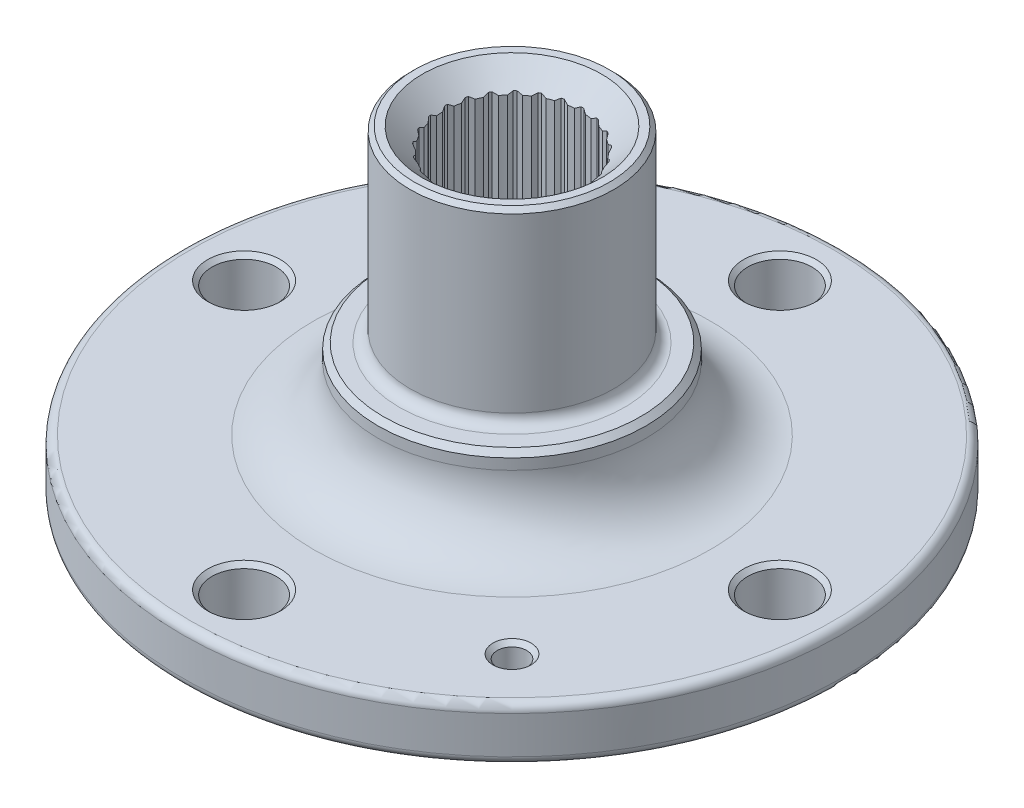
SolidWorks part; units mm, degrees
ref_plane "Plano frontal" through (0, 0, 0) normal (0, 0, 1) x (1, 0, 0)
ref_plane "Plano superior" through (0, 0, 0) normal (0, 1, 0) x (1, 0, 0)
ref_plane "Plano direito" through (0, 0, 0) normal (1, 0, 0) x (0, 0, -1)
sketch "Esboço1" plane through (0, 0, 0) normal (0, 0, 1) x (1, 0, 0)
  line L0 (0, -42.6779) -> (0, 53.2086) construction
  line L1 (12.75, 53.2086) -> (19, 53.2086)
  line L2 (19, 53.2086) -> (19, 18.2086)
  line L3 (19, 18.2086) -> (25, 18.2086)
  line L4 (25, 18.2086) -> (25, 3.2086)
  line L5 (25, 3.2086) -> (61.5, 3.2086)
  line L6 (61.5, 3.2086) -> (61.5, -6.7914)
  line L7 (61.5, -6.7914) -> (31, -6.7914)
  line L8 (31, -6.7914) -> (31, -12.7914)
  line L9 (31, -12.7914) -> (27, -12.7914)
  line L10 (27, -12.7914) -> (27, -23.7914)
  line L11 (27, -23.7914) -> (24, -23.7914)
  line L12 (24, -23.7914) -> (24, 0)
  line L13 (24, 0) -> (12.75, 0)
  line L14 (12.75, 0) -> (12.75, 53.2086)
  dimension "D1" = 12.75
  dimension "D2" = 19
  dimension "D3" = 35
  dimension "D4" = 50
  dimension "D5" = 61.5
  dimension "D6" = 24
  dimension "D7" = 31
  dimension "D8" = 27
  dimension "D9" = 10
  dimension "D10" = 6
  dimension "D11" = 17
  dimension "D12" = 25
revolve "Revolução1" add sketch "Esboço1" angle 360 about L0
fillet "Filete1" radius 12 1 edges at (0, 3.2086, -25)
fillet "Filete2" radius 2 1 edges at (0, 18.2086, -19)
chamfer "Chanfro1" distance 0.8 angle 45 1 edges at (0, 53.2086, -19)
sketch "Esboço2" plane through (0, -6.7914, 0) normal (0, -1, 0) x (1, 0, 0)
  circle A0 centre (0, 0) radius 50 construction
  circle A1 centre (0, 50) radius 6
  circle A2 centre (-35.3553, -35.3553) radius 2.75
  circle A3 centre (50, 0) radius 6
  circle A4 centre (35.3553, 35.3553) radius 2.75
  circle A5 centre (0, -50) radius 6
  circle A7 centre (-50, 0) radius 6
  circle A9 centre (-35.3553, 35.3553) radius 6 [skipped]
  circle A10 centre (35.3553, -35.3553) radius 6 [skipped]
  circle A11 centre (35.3553, 35.3553) radius 6 [skipped]
  circle A12 centre (-35.3553, -35.3553) radius 6 [skipped]
  point P21 (0, 0)
  dimension "D1" = 100
  dimension "D2" = 12
  dimension "D4" = 5.5
  dimension "D3" = 8
extrude "Corte-extrusão1" cut sketch "Esboço2" against normal through all
chamfer "Chanfro2" distance 0.8 angle 45 12 edges at (0, -6.7914, -56) (0, 3.2086, -44) (50, -6.7914, -6) (50, 3.2086, 6) (35.3553, 3.2086, 38.1053) (35.3553, -6.7914, 32.6053) (-35.3553, -6.7914, -38.1053) (-35.3553, 3.2086, -32.6053) (-50, -6.7914, -6) (-50, 3.2086, 6) (0, -6.7914, 44) (0, 3.2086, 56)
fillet "Filete3" radius 1.5 1 edges at (0, -6.7914, -61.5)
fillet "Filete4" radius 1.5 1 edges at (0, 3.2086, -61.5)
chamfer "Chanfro3" distance 1 angle 45 1 edges at (0, 18.2086, -25)
fillet "Filete5" radius 1.5 1 edges at (0, -6.7914, -31)
chamfer "Chanfro4" distance 0.8 angle 45 3 edges at (0, -23.7914, -24) (0, -23.7914, -27) (0, -12.7914, -31)
fillet "Filete6" radius 2 1 edges at (0, -12.7914, -27)
chamfer "Chanfro5" distance 4 angle 45 1 edges at (0, 53.2086, -12.75)
chamfer "Chanfro6" distance 0.5 angle 30 1 edges at (0, 0, -12.75)
fillet "Filete7" radius 1.5 1 edges at (0, 0, -24)
sketch "Esboço3" plane through (0, 53.2086, 0) normal (0, 1, 0) x (1, 0, 0)
sketch "Esboço4" plane through (0, 53.2086, 0) normal (0, 1, 0) x (1, 0, 0)
  line L0 (2.1924, 12.5601) -> (3.0275, 12.7967)
  line L1 (-1, 12.7107) -> (-0.25, 13.1476)
  line L2 (0.25, 13.1476) -> (1, 12.7107)
  line L3 (3.5118, 12.6724) -> (4.1296, 12.0627)
  line L4 (5.2471, 11.6202) -> (6.1148, 11.6418)
  line L5 (6.553, 11.4009) -> (6.9997, 10.6567)
  line L6 (7.9721, 9.9503) -> (8.8179, 9.7553)
  line L7 (9.1824, 9.4131) -> (9.4301, 8.5812)
  line L8 (10.1962, 7.6551) -> (10.9669, 7.2559)
  line L9 (11.2349, 6.8338) -> (11.2678, 5.9664)
  line L10 (11.7796, 4.8789) -> (12.4269, 4.3006)
  line L11 (12.5814, 3.8251) -> (12.3976, 2.9768)
  line L12 (12.6229, 1.7961) -> (13.106, 1.0751)
  line L13 (13.1374, 0.576) -> (12.7484, -0.1999)
  line L14 (12.673, -1.3995) -> (12.9616, -2.218)
  line L15 (12.8679, -2.7092) -> (12.2982, -3.364)
  line L16 (11.9268, -4.5071) -> (12.0028, -5.3718)
  line L17 (11.7899, -5.8242) -> (11.0752, -6.3168)
  line L18 (10.4312, -7.3316) -> (10.2898, -8.188)
  line L19 (9.9711, -8.5732) -> (9.1564, -8.8726)
  line L20 (8.2802, -9.6954) -> (7.9302, -10.4897)
  line L21 (7.5257, -10.7836) -> (6.6622, -10.871)
  line L22 (5.6089, -11.45) -> (5.0724, -12.1323)
  line L23 (4.6075, -12.3164) -> (3.7494, -12.1863)
  line L24 (2.5852, -12.4852) -> (1.8959, -13.0126)
  line L25 (1.3998, -13.0753) -> (0.601, -12.7358)
  line L26 (-0.601, -12.7358) -> (-1.3998, -13.0753)
  line L27 (-1.8959, -13.0126) -> (-2.5852, -12.4852)
  line L28 (-3.7494, -12.1863) -> (-4.6075, -12.3164)
  line L29 (-5.0724, -12.1323) -> (-5.6089, -11.45)
  line L30 (-6.6622, -10.871) -> (-7.5257, -10.7836)
  line L31 (-7.9302, -10.4897) -> (-8.2802, -9.6954)
  line L32 (-9.1564, -8.8726) -> (-9.9711, -8.5732)
  line L33 (-10.2898, -8.188) -> (-10.4312, -7.3316)
  line L34 (-11.0752, -6.3168) -> (-11.7899, -5.8242)
  line L35 (-12.0028, -5.3718) -> (-11.9268, -4.5071)
  line L36 (-12.2982, -3.364) -> (-12.8679, -2.7092)
  line L37 (-12.9616, -2.218) -> (-12.673, -1.3995)
  line L38 (-12.7484, -0.1999) -> (-13.1374, 0.576)
  line L39 (-13.106, 1.0751) -> (-12.6229, 1.7961)
  line L40 (-12.3976, 2.9768) -> (-12.5814, 3.8251)
  line L41 (-12.4269, 4.3006) -> (-11.7796, 4.8789)
  line L42 (-11.2678, 5.9664) -> (-11.2349, 6.8338)
  line L43 (-10.9669, 7.2559) -> (-10.1962, 7.6551)
  line L44 (-9.4301, 8.5812) -> (-9.1824, 9.4131)
  line L45 (-8.8179, 9.7553) -> (-7.9721, 9.9503)
  line L46 (-6.9997, 10.6567) -> (-6.553, 11.4009)
  line L47 (-6.1148, 11.6418) -> (-5.2471, 11.6202)
  line L48 (-4.1296, 12.0627) -> (-3.5118, 12.6724)
  line L49 (-3.0275, 12.7967) -> (-2.1924, 12.5601)
  arc A0 (3.0275, 12.7967) -> (3.5118, 12.6724) centre (0, 0) cw
  arc A1 (-0.25, 13.1476) -> (0.25, 13.1476) centre (0, 0) cw
  arc A2 (-1, 12.7107) -> (1, 12.7107) centre (0, 0) cw
  arc A3 (2.1924, 12.5601) -> (4.1296, 12.0627) centre (0, 0) cw
  arc A4 (6.1148, 11.6418) -> (6.553, 11.4009) centre (0, 0) cw
  arc A5 (5.2471, 11.6202) -> (6.9997, 10.6567) centre (0, 0) cw
  arc A6 (8.8179, 9.7553) -> (9.1824, 9.4131) centre (0, 0) cw
  arc A7 (7.9721, 9.9503) -> (9.4301, 8.5812) centre (0, 0) cw
  arc A8 (10.9669, 7.2559) -> (11.2349, 6.8338) centre (0, 0) cw
  arc A9 (10.1962, 7.6551) -> (11.2678, 5.9664) centre (0, 0) cw
  arc A10 (12.4269, 4.3006) -> (12.5814, 3.8251) centre (0, 0) cw
  arc A11 (11.7796, 4.8789) -> (12.3976, 2.9768) centre (0, 0) cw
  arc A12 (13.106, 1.0751) -> (13.1374, 0.576) centre (0, 0) cw
  arc A13 (12.6229, 1.7961) -> (12.7484, -0.1999) centre (0, 0) cw
  arc A14 (12.9616, -2.218) -> (12.8679, -2.7092) centre (0, 0) cw
  arc A15 (12.673, -1.3995) -> (12.2982, -3.364) centre (0, 0) cw
  arc A16 (12.0028, -5.3718) -> (11.7899, -5.8242) centre (0, 0) cw
  arc A17 (11.9268, -4.5071) -> (11.0752, -6.3168) centre (0, 0) cw
  arc A18 (10.2898, -8.188) -> (9.9711, -8.5732) centre (0, 0) cw
  arc A19 (10.4312, -7.3316) -> (9.1564, -8.8726) centre (0, 0) cw
  arc A20 (7.9302, -10.4897) -> (7.5257, -10.7836) centre (0, 0) cw
  arc A21 (8.2802, -9.6954) -> (6.6622, -10.871) centre (0, 0) cw
  arc A22 (5.0724, -12.1323) -> (4.6075, -12.3164) centre (0, 0) cw
  arc A23 (5.6089, -11.45) -> (3.7494, -12.1863) centre (0, 0) cw
  arc A24 (1.8959, -13.0126) -> (1.3998, -13.0753) centre (0, 0) cw
  arc A25 (2.5852, -12.4852) -> (0.601, -12.7358) centre (0, 0) cw
  arc A26 (-1.3998, -13.0753) -> (-1.8959, -13.0126) centre (0, 0) cw
  arc A27 (-0.601, -12.7358) -> (-2.5852, -12.4852) centre (0, 0) cw
  arc A28 (-4.6075, -12.3164) -> (-5.0724, -12.1323) centre (0, 0) cw
  arc A29 (-3.7494, -12.1863) -> (-5.6089, -11.45) centre (0, 0) cw
  arc A30 (-7.5257, -10.7836) -> (-7.9302, -10.4897) centre (0, 0) cw
  arc A31 (-6.6622, -10.871) -> (-8.2802, -9.6954) centre (0, 0) cw
  arc A32 (-9.9711, -8.5732) -> (-10.2898, -8.188) centre (0, 0) cw
  arc A33 (-9.1564, -8.8726) -> (-10.4312, -7.3316) centre (0, 0) cw
  arc A34 (-11.7899, -5.8242) -> (-12.0028, -5.3718) centre (0, 0) cw
  arc A35 (-11.0752, -6.3168) -> (-11.9268, -4.5071) centre (0, 0) cw
  arc A36 (-12.8679, -2.7092) -> (-12.9616, -2.218) centre (0, 0) cw
  arc A37 (-12.2982, -3.364) -> (-12.673, -1.3995) centre (0, 0) cw
  arc A38 (-13.1374, 0.576) -> (-13.106, 1.0751) centre (0, 0) cw
  arc A39 (-12.7484, -0.1999) -> (-12.6229, 1.7961) centre (0, 0) cw
  arc A40 (-12.5814, 3.8251) -> (-12.4269, 4.3006) centre (0, 0) cw
  arc A41 (-12.3976, 2.9768) -> (-11.7796, 4.8789) centre (0, 0) cw
  arc A42 (-11.2349, 6.8338) -> (-10.9669, 7.2559) centre (0, 0) cw
  arc A43 (-11.2678, 5.9664) -> (-10.1962, 7.6551) centre (0, 0) cw
  arc A44 (-9.1824, 9.4131) -> (-8.8179, 9.7553) centre (0, 0) cw
  arc A45 (-9.4301, 8.5812) -> (-7.9721, 9.9503) centre (0, 0) cw
  arc A46 (-6.553, 11.4009) -> (-6.1148, 11.6418) centre (0, 0) cw
  arc A47 (-6.9997, 10.6567) -> (-5.2471, 11.6202) centre (0, 0) cw
  arc A48 (-3.5118, 12.6724) -> (-3.0275, 12.7967) centre (0, 0) cw
  arc A49 (-4.1296, 12.0627) -> (-2.1924, 12.5601) centre (0, 0) cw
  point P105 (0, 0)
  dimension "D1" = 25
extrude "Corte-extrusão2" cut sketch "Esboço4" against normal through all
